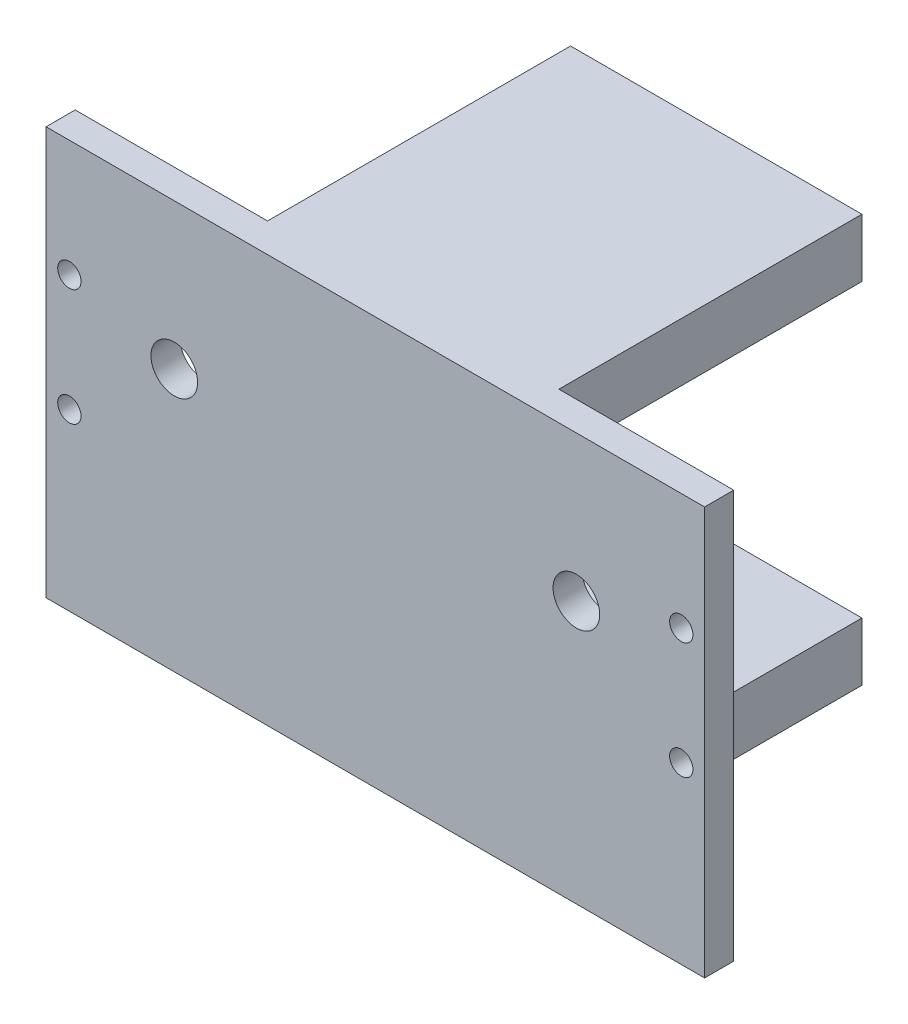
SolidWorks part; units mm, degrees
ref_plane "前视基准面" through (0, 0, 0) normal (0, 0, 1) x (1, 0, 0)
ref_plane "上视基准面" through (0, 0, 0) normal (0, 1, 0) x (1, 0, 0)
ref_plane "右视基准面" through (0, 0, 0) normal (1, 0, 0) x (0, 0, -1)
sketch "草图1" plane through (0, 0, 0) normal (0, 0, 1) x (1, 0, 0)
  line L1 (-56.5, 35) -> (56.5, 35)
  line L2 (-56.5, 35) -> (-56.5, -35)
  line L3 (-56.5, -35) -> (56.5, -35)
  line L4 (56.5, 35) -> (56.5, -35)
  line L5 (-56.5, 35) -> (56.5, -35) construction
  line L6 (-56.5, -35) -> (56.5, 35) construction
  point P0 (0, 0)
  dimension "D1" = 113
  dimension "D2" = 70
extrude "凸台-拉伸1" add sketch "草图1" along normal blind 5 contours L1 L4 L3 L2
sketch "草图2" plane through (0, 0, 0) normal (0, 0, -1) x (-1, 0, 0)
  line L0 (56.5, -35) -> (-56.5, -35) construction
  line L1 (-56.5, 35) -> (-56.5, -35) construction
  line L2 (56.5, 35) -> (-56.5, 35) construction
  line L3 (-26.5, -35) -> (23.5, -35)
  line L4 (-26.5, -35) -> (-26.5, -25)
  line L5 (-26.5, -25) -> (23.5, -25)
  line L6 (23.5, -35) -> (23.5, -25)
  line L7 (-26.5, 35) -> (23.5, 35)
  line L8 (-26.5, 35) -> (-26.5, 25)
  line L9 (-26.5, 25) -> (23.5, 25)
  line L10 (23.5, 35) -> (23.5, 25)
  point P0 (-26.5, -35)
  dimension "D1" = 30
  dimension "D2" = 50
  dimension "D3" = 10
  dimension "D4" = 30
  dimension "D5" = 50
  dimension "D6" = 10
extrude "凸台-拉伸2" add sketch "草图2" along normal blind 52
sketch "草图3" plane through (0, 0, 0) normal (0, 0, -1) x (-1, 0, 0)
  line L0 (-26.5, 35) -> (-56.5, 35) construction
  line L2 (-56.5, 35) -> (-56.5, -35) construction
  line L3 (56.5, 35) -> (23.5, 35) construction
  line L4 (56.5, 35) -> (56.5, -35) construction
  circle A0 centre (-34.5, 10) radius 4
  circle A1 centre (34.5, 10) radius 4
  point P0 (-34.5, 10)
  point P9 (40, 35)
  dimension "D3" = 25
  dimension "D1" = 25
  dimension "D2" = 22
  dimension "D4" = 22
extrude "切除-拉伸1" cut sketch "草图3" against normal through all
sketch "草图5" plane through (0, 0, 5) normal (0, 0, 1) x (1, 0, 0)
  line L0 (-56.5, 35) -> (56.5, 35) construction
  line L1 (-56.5, 35) -> (-56.5, -35) construction
  circle A0 centre (-52.5, 15) radius 2
  circle A1 centre (52.5, 15) radius 2
  circle A2 centre (52.5, -5) radius 2
  circle A3 centre (-52.5, -5) radius 2
  point P0 (-52.5, 15)
  dimension "D1" = 20
  dimension "D2" = 4
  dimension "D5" = 105
  dimension "D3" = 2
  dimension "D4" = 2
extrude "切除-拉伸2" cut sketch "草图5" against normal through all
